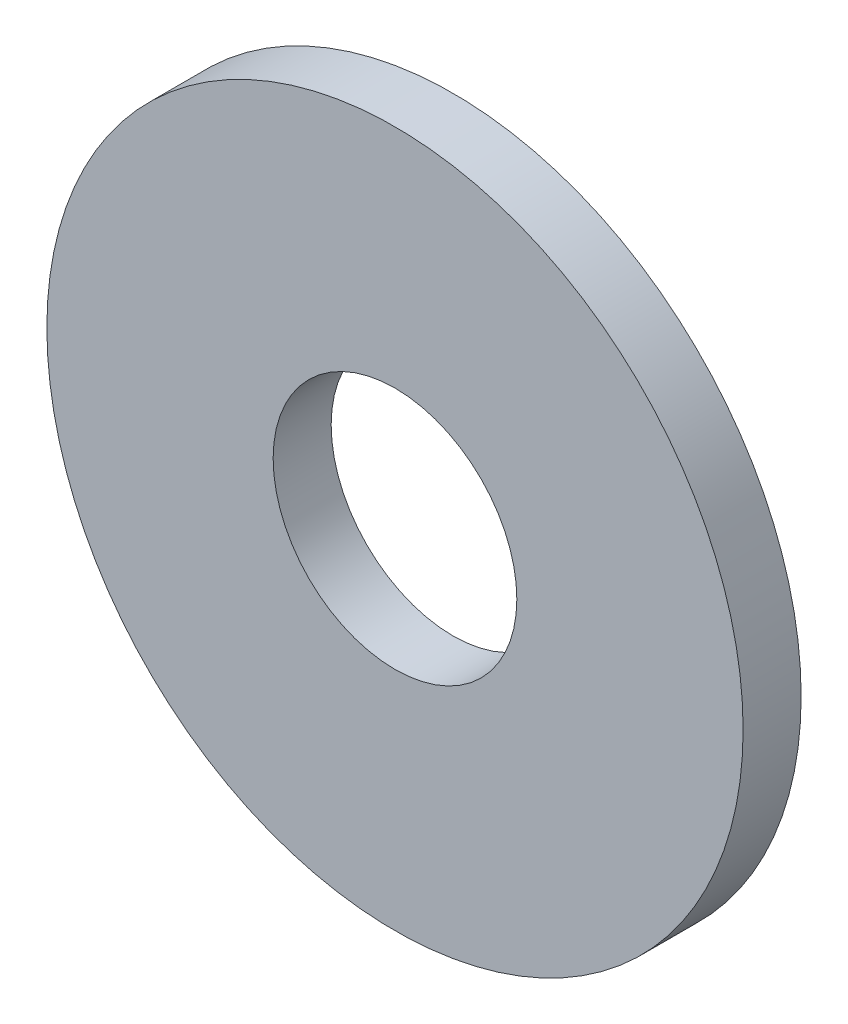
SolidWorks part; units mm, degrees
ref_plane "Front Plane" through (0, 0, 0) normal (0, 0, 1) x (1, 0, 0)
ref_plane "Top Plane" through (0, 0, 0) normal (0, 1, 0) x (1, 0, 0)
ref_plane "Right Plane" through (0, 0, 0) normal (1, 0, 0) x (0, 0, -1)
sketch "Sketch1" plane through (0, 0, 0) normal (1, 0, 0) x (0, 0, -1)
  line L0 (0, -12) -> (0, 12) construction
  line L1 (0, -4.2) -> (0, 4.2) construction
  line L2 (-1, 0) -> (1, 0) construction
  point P4 (0, 0)
  point P8 (0, 0)
  point P11 (0, 0)
sketch "Sketch2" plane through (0, 0, 0) normal (0, 0, 1) x (1, 0, 0)
  circle A0 centre (0, 0) radius 12
  circle A1 centre (0, 0) radius 4.2
extrude "Boss-Extrude1" add sketch "Sketch2" along normal mid plane 2
equation "\"D1@Boss-Extrude1\" = \"Thickness@Sketch1\""
